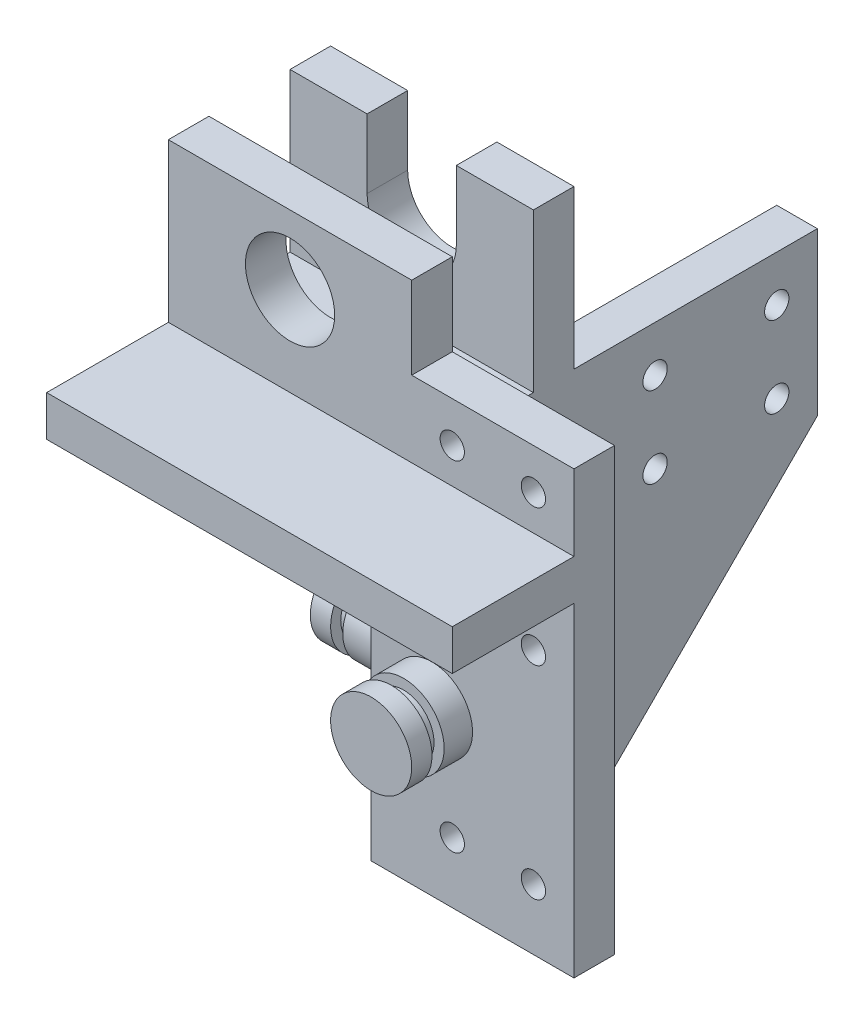
SolidWorks part; units mm, degrees
ref_plane "Front Plane" through (0, 0, 0) normal (0, 0, 1) x (1, 0, 0)
ref_plane "Top Plane" through (0, 0, 0) normal (0, 1, 0) x (1, 0, 0)
ref_plane "Right Plane" through (0, 0, 0) normal (1, 0, 0) x (0, 0, -1)
sketch "Sketch1" plane through (0, 0, 0) normal (0, 1, 0) x (1, 0, 0)
  line L0 (0, 0) -> (100, 0)
  line L1 (100, 0) -> (100, 40)
  line L2 (100, 40) -> (60, 40)
  line L3 (60, 40) -> (60, 80)
  line L4 (60, 80) -> (0, 80)
  line L5 (0, 80) -> (0, 0)
  dimension "D1" = 40
  dimension "D2" = 40
  dimension "D3" = 100
  dimension "D4" = 40
extrude "Boss-Extrude1" add sketch "Sketch1" along normal blind 10
sketch "Sketch2" plane through (0, 0, 0) normal (0, -1, 0) x (1, 0, 0)
  line L0 (60, -40) -> (100, -40)
  line L1 (100, -40) -> (100, -30)
  line L2 (100, 0) -> (100, -40) construction
  line L3 (100, -30) -> (50, -30)
  line L4 (50, -30) -> (50, -80)
  line L5 (60, -80) -> (0, -80) construction
  line L6 (50, -80) -> (60, -80)
  line L7 (60, -80) -> (60, -40)
  dimension "D1" = 10
  dimension "D2" = 10
extrude "Boss-Extrude2" add sketch "Sketch2" along normal blind 80
sketch "Sketch3" plane through (0, 10, 0) normal (0, 1, 0) x (1, 0, 0)
  line L0 (60, 40) -> (60, 80) construction
  line L1 (100, 40) -> (60, 40)
  line L2 (100, 40) -> (100, 30)
  line L3 (100, 30) -> (60, 30)
  line L4 (60, 40) -> (60, 30)
  dimension "D1" = 10
extrude "Boss-Extrude3" add sketch "Sketch3" along normal blind 18.71
sketch "Sketch4" plane through (0, 0, -80) normal (0, 0, -1) x (-1, 0, 0)
  line L0 (-60, 10) -> (-60, -80)
  line L1 (-60, 10) -> (-60, -80) construction
  line L2 (-60, -80) -> (-50, -80)
  line L3 (-50, -80) -> (-50, 0) construction
  line L4 (-50, -80) -> (-50, 10)
  line L5 (-60, 10) -> (0, 10) construction
  line L6 (-50, 10) -> (-60, 10)
  line L7 (-50, -80) -> (-60, -80) construction
extrude "Boss-Extrude4" add sketch "Sketch4" along normal blind 50
sketch "Sketch5" plane through (50, 0, 0) normal (-1, 0, 0) x (0, 0, 1)
  line L0 (-80, 10) -> (-80, -80) construction
  line L1 (-30, -80) -> (-130, -80) construction
  line L2 (-80, -80) -> (-130, -30)
  line L3 (-130, -80) -> (-130, 10) construction
  line L7 (-130, -30) -> (-130, -80)
  line L8 (-130, -80) -> (-80, -80)
  dimension "D1" = 50
extrude "Cut-Extrude1" cut sketch "Sketch5" against normal up to next
sketch "Sketch6" plane through (0, 10, 0) normal (0, 1, 0) x (1, 0, 0)
  line L0 (50, 80) -> (0, 80) construction
  line L1 (0, 80) -> (0, 0) construction
  circle A0 centre (7, 50) radius 3.5
  circle A1 centre (53, 50) radius 3.5
  point P4 (0, 0)
  dimension "D1" = 7
  dimension "D2" = 30
  dimension "D3" = 7
  dimension "D4" = 46
extrude "Cut-Extrude2" cut sketch "Sketch6" against normal blind 10
sketch "Sketch7" plane through (50, 0, 0) normal (-1, 0, 0) x (0, 0, 1)
  line L0 (-50, 0) -> (-43, 0)
  line L1 (-48.1972, 0) -> (-51.8028, 0) construction
  line L2 (-80, 0) -> (0, 0) construction
  line L3 (-43, 0) -> (-43, -6)
  line L4 (-43, -6) -> (-57, -6)
  line L5 (-57, -6) -> (-57, 0)
  line L6 (-57, 0) -> (-50, 0)
  dimension "D1" = 14
  dimension "D2" = 7
  dimension "D3" = 6
extrude "Cut-Extrude3" cut sketch "Sketch7" against normal blind 10
sketch "Sketch8" plane through (0, 0, -30) normal (0, 0, 1) x (1, 0, 0)
  line L0 (60, 28.71) -> (100, 28.71) construction
  line L1 (100, 28.71) -> (100, 10) construction
  line L3 (100, -80) -> (50, -80) construction
  circle A0 centre (70, 18.71) radius 3
  circle A1 centre (90, 18.71) radius 3
  circle A2 centre (70, -15) radius 3
  circle A3 centre (90, -15) radius 3
  circle A4 centre (90, -65) radius 3
  circle A5 centre (70, -65) radius 3
  point P14 (0, 0)
  point P15 (0, 0)
  point P16 (0, 0)
  point P17 (0, 0)
  point P18 (0, 0)
  point P21 (90, -14.0756)
  point P26 (0, 0)
  point P27 (0, 0)
  dimension "D4" = 6
  dimension "D1" = 10
  dimension "D2" = 10
  dimension "D3" = 20
  dimension "D5" = 50
  dimension "D6" = 15
extrude "Cut-Extrude4" cut sketch "Sketch8" against normal blind 10
sketch "Sketch9" plane through (50, 0, 0) normal (-1, 0, 0) x (0, 0, 1)
  line L0 (-30, -80) -> (-30, 0) construction
  line L1 (-80, 0) -> (0, 0) construction
  line L2 (-30, -80) -> (-80, -80) construction
  line L3 (-130, 10) -> (-80, 10) construction
  line L4 (-130, -30) -> (-130, 10) construction
  circle A0 centre (-50, -15) radius 3
  circle A1 centre (-70, -15) radius 3
  circle A2 centre (-70, -65) radius 3
  circle A3 centre (-50, -65) radius 3
  circle A4 centre (-90, -1.3) radius 3
  circle A5 centre (-120, -1.3) radius 3
  circle A6 centre (-90, -21.3) radius 3
  circle A7 centre (-120, -21.3) radius 3
  point P22 (0, 0)
  point P23 (0, 0)
  point P24 (0, 0)
  point P25 (0, 0)
  dimension "D1" = 6
  dimension "D2" = 20
  dimension "D3" = 20
  dimension "D4" = 15
  dimension "D5" = 15
  dimension "D6" = 11.3
  dimension "D7" = 20
  dimension "D8" = 10
  dimension "D9" = 30
extrude "Cut-Extrude5" cut sketch "Sketch9" against normal blind 10
sketch "Sketch10" plane through (0, 10, 0) normal (0, 1, 0) x (1, 0, 0)
  line L0 (0, 80) -> (0, 0) construction
  line L1 (0, 40) -> (60, 40)
  line L2 (0, 40) -> (0, 30)
  line L3 (0, 30) -> (60, 30)
  line L4 (60, 40) -> (60, 30)
  line L5 (60, 40) -> (60, 30) construction
  line L6 (0, 0) -> (100, 0) construction
  line L7 (60, 40) -> (60, 130) construction
  line L8 (0, 70) -> (60, 70)
  line L9 (0, 70) -> (0, 60)
  line L10 (0, 60) -> (60, 60)
  line L11 (60, 70) -> (60, 60)
  dimension "D1" = 10
  dimension "D2" = 30
  dimension "D3" = 10
  dimension "D4" = 20
extrude "Boss-Extrude5" add sketch "Sketch10" along normal blind 39
sketch "Sketch11" plane through (0, 0, -30) normal (0, 0, 1) x (1, 0, 0)
  line L0 (0, 10) -> (100, 10) construction
  line L1 (0, 49) -> (0, 10) construction
  circle A0 centre (30, 32) radius 11
  dimension "D2" = 22
  dimension "D1" = 22
  dimension "D3" = 30
extrude "Cut-Extrude6" cut sketch "Sketch11" against normal blind 10
sketch "Sketch12" plane through (0, 0, -70) normal (0, 0, -1) x (-1, 0, 0)
  line L0 (-19, 49) -> (-19, 32)
  line L1 (-60, 49) -> (0, 49) construction
  line L2 (-19, 49) -> (-41, 49)
  line L3 (-41, 49) -> (-41, 32)
  line L4 (0, 49) -> (0, 10) construction
  line L5 (-60, 10) -> (0, 10) construction
  arc A0 (-19, 32) -> (-41, 32) centre (-30, 32) cw
  point P7 (0, 0)
  point P8 (-30, 49)
  point P11 (0, 0)
  point P12 (-19, 29.6654)
  dimension "D4" = 11
  dimension "D1" = 22
  dimension "D2" = 30
  dimension "D3" = 30
  dimension "D5" = 22
extrude "Cut-Extrude7" cut sketch "Sketch12" against normal blind 10
sketch "Sketch13" plane through (0, 0, -30) normal (0, 0, 1) x (1, 0, 0)
  line L0 (50, -80) -> (50, 0) construction
  line L1 (100, -80) -> (50, -80) construction
  circle A0 centre (65, -40) radius 10
  dimension "D3" = 20
  dimension "D1" = 15
  dimension "D2" = 40
extrude "Boss-Extrude6" add sketch "Sketch13" along normal blind 15
sketch "Sketch14" plane through (0, 0, -15) normal (0, 0, 1) x (1, 0, 0)
  circle A0 centre (65, -40) radius 7.5
  circle A1 centre (65, -40) radius 10
  dimension "D1" = 15
extrude "Cut-Extrude8" cut sketch "Sketch14" against normal blind 3 from offset 5 offset against normal yes
sketch "Sketch15" plane through (50, 0, 0) normal (-1, 0, 0) x (0, 0, 1)
  line L0 (-30, -80) -> (-80, -80) construction
  line L1 (-30, -80) -> (-30, 0) construction
  circle A0 centre (-45, -40) radius 10
  dimension "D3" = 20
  dimension "D1" = 40
  dimension "D2" = 15
extrude "Boss-Extrude7" add sketch "Sketch15" along normal blind 20
sketch "Sketch16" plane through (30, 0, 0) normal (-1, 0, 0) x (0, 0, 1)
  circle A0 centre (-45, -40) radius 7.5
  circle A1 centre (-45, -40) radius 10
  dimension "D1" = 20
  dimension "D2" = 15
extrude "Cut-Extrude9" cut sketch "Sketch16" against normal blind 3 from offset 5
